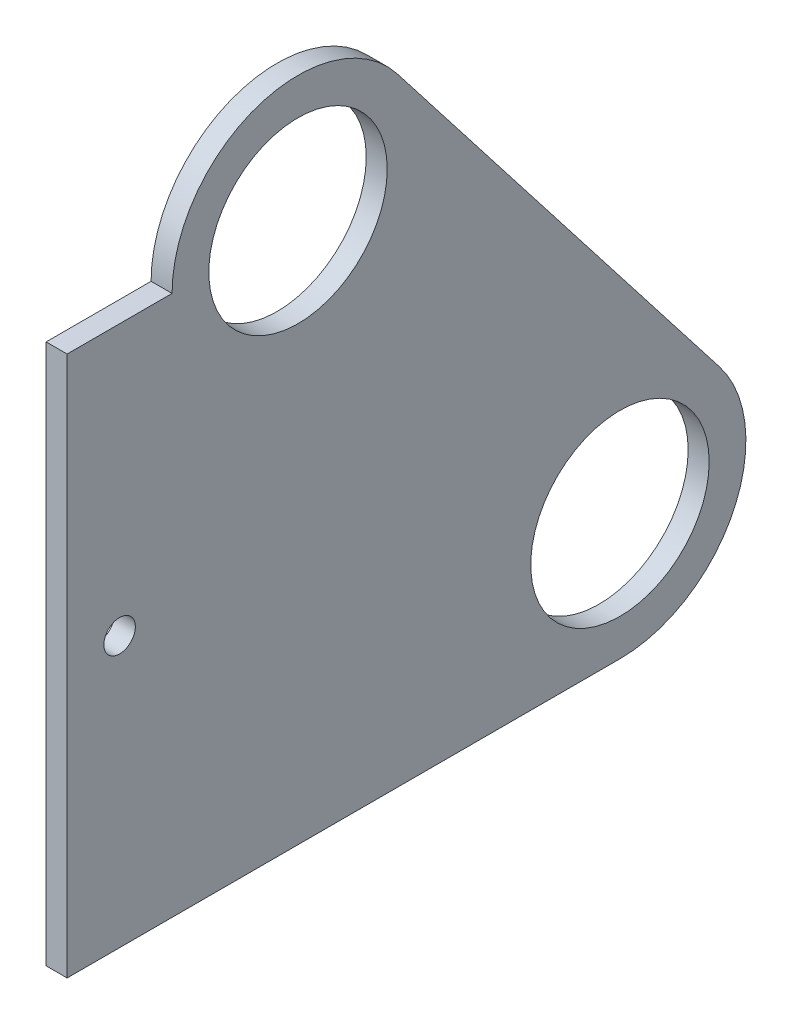
SolidWorks part; units mm, degrees
ref_plane "前视基准面" through (0, 0, 0) normal (0, 0, 1) x (1, 0, 0)
ref_plane "上视基准面" through (0, 0, 0) normal (0, 1, 0) x (1, 0, 0)
ref_plane "右视基准面" through (0, 0, 0) normal (1, 0, 0) x (0, 0, -1)
sketch "草图1" plane through (0, 0, 0) normal (1, 0, 0) x (0, 0, -1)
  line L0 (0, 0) -> (-30.6729, 39.4863) construction
  line L1 (-30.6729, 39.4863) -> (-30.6729, 0) construction
  line L2 (-30.6729, 0) -> (0, 0) construction
  line L3 (-21.1962, 46.8478) -> (9.4767, 7.3615)
  line L4 (-42.6729, 39.4863) -> (-52.6729, 39.4863)
  line L5 (-52.6729, 39.4863) -> (-52.6729, -12)
  line L6 (-52.6729, -12) -> (0, -12)
  circle A0 centre (0, 0) radius 8.5
  circle A1 centre (0, 0) radius 12 construction
  circle A2 centre (-30.6729, 39.4863) radius 8.5
  circle A3 centre (-30.6729, 39.4863) radius 12 construction
  arc A4 (-42.6729, 39.4863) -> (-21.1962, 46.8478) centre (-30.6729, 39.4863) cw
  arc A5 (9.4767, 7.3615) -> (0, -12) centre (0, 0) cw
  dimension "D1" = 10
  dimension "D2" = 24
  dimension "D3" = 17
  dimension "D4" = 17
  dimension "D5" = 24
  dimension "D6" = 50
extrude "凸台-拉伸1" add sketch "草图1" along normal blind 2 contours A5 L3 A4 L4 L5 L6 A2 A0
sketch "草图2" plane through (2, 0, 0) normal (1, 0, 0) x (0, 0, -1)
  line L0 (-52.6729, 13.7432) -> (-47.6729, 13.7432) construction
  line L1 (-52.6729, 39.4863) -> (-52.6729, -12) construction
  circle A0 centre (-47.6729, 13.7432) radius 1.5
  dimension "D1" = 5
extrude "切除-拉伸1" cut sketch "草图2" against normal blind 10
